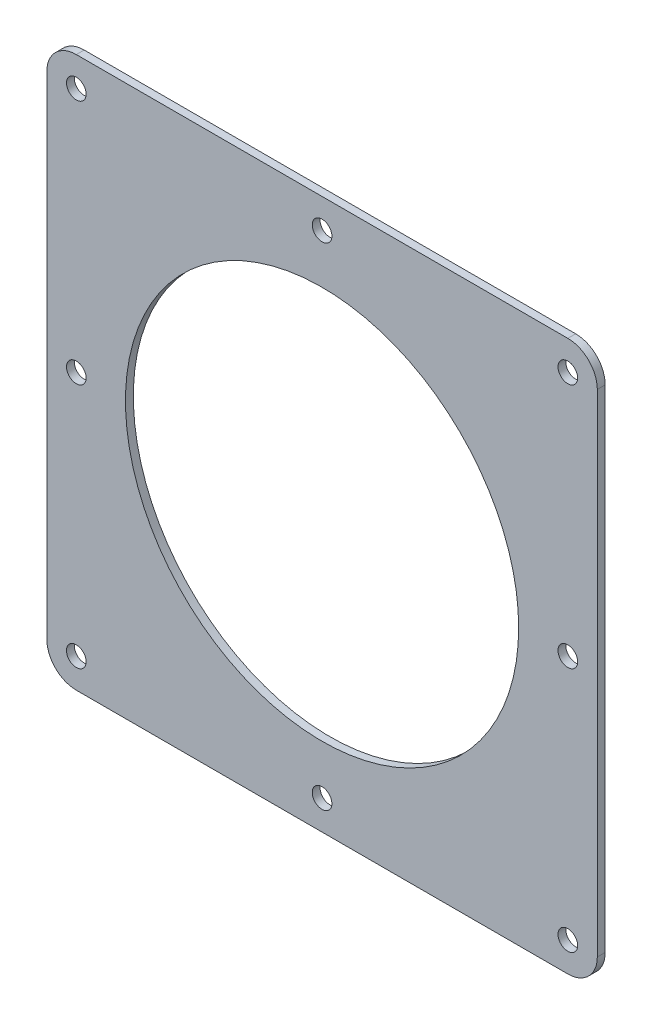
SolidWorks part; units mm, degrees
ref_plane "Front Plane" through (0, 0, 0) normal (0, 0, 1) x (1, 0, 0)
ref_plane "Top Plane" through (0, 0, 0) normal (0, 1, 0) x (1, 0, 0)
ref_plane "Right Plane" through (0, 0, 0) normal (1, 0, 0) x (0, 0, -1)
sketch "Sketch2" plane through (0, 0, 0) normal (0, 0, 1) x (1, 0, 0)
  line L0 (-125, 125) -> (125, 125) construction
  line L1 (-125, 140) -> (125, 140)
  line L2 (-140, 125) -> (-140, -125)
  line L3 (-125, -140) -> (125, -140)
  line L4 (140, 125) -> (140, -125)
  line L5 (-140, 140) -> (140, -140) construction
  line L6 (-140, -140) -> (140, 140) construction
  line L7 (125, 125) -> (125, -125) construction
  line L8 (125, -125) -> (-125, -125) construction
  line L9 (-125, -125) -> (-125, 125) construction
  arc A0 (-140, -125) -> (-125, -140) centre (-125, -125) ccw
  arc A1 (125, -140) -> (140, -125) centre (125, -125) ccw
  arc A2 (125, 140) -> (140, 125) centre (125, 125) cw
  arc A3 (-125, 140) -> (-140, 125) centre (-125, 125) ccw
  circle A4 centre (-125, 125) radius 5
  circle A5 centre (0, 125) radius 5
  circle A6 centre (125, 125) radius 5
  circle A13 centre (0, 0) radius 4
  circle A14 centre (125, 0) radius 5
  circle A15 centre (-125, 0) radius 5
  circle A16 centre (-125, -125) radius 5
  circle A17 centre (0, -125) radius 5
  circle A18 centre (125, -125) radius 5
  point P0 (0, 0)
  dimension "D3" = 15
  dimension "D4" = 10
  dimension "D5" = 10
  dimension "D6" = 10
  dimension "D7" = 8
  dimension "D8" = 10
  dimension "D9" = 10
  dimension "D10" = 10
  dimension "D11" = 10
  dimension "D1" = 280
  dimension "D2" = 280
extrude "Boss-Extrude1" add sketch "Sketch2" along normal blind 4
sketch "Sketch7" plane through (0, 0, 4) normal (0, 0, 1) x (1, 0, 0)
  circle A0 centre (0, 0) radius 100
  dimension "D1" = 200
extrude "Cut-Extrude2" cut sketch "Sketch7" against normal blind 10
